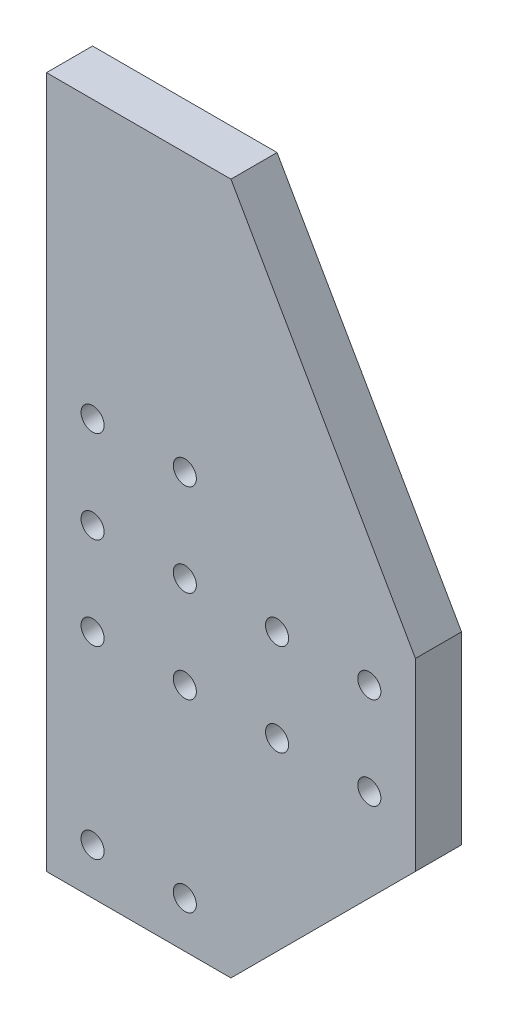
SolidWorks part; units mm, degrees
ref_plane "Front Plane" through (0, 0, 0) normal (0, 0, 1) x (1, 0, 0)
ref_plane "Top Plane" through (0, 0, 0) normal (0, 1, 0) x (1, 0, 0)
ref_plane "Right Plane" through (0, 0, 0) normal (1, 0, 0) x (0, 0, -1)
sketch "Sketch1" plane through (0, 0, 0) normal (0, 0, 1) x (1, 0, 0)
  line L0 (0, 0) -> (40, 0)
  line L1 (40, 0) -> (80, 40)
  line L2 (80, 40) -> (80, 80)
  line L3 (80, 80) -> (40, 150)
  line L4 (40, 150) -> (0, 150)
  line L5 (0, 150) -> (0, 0)
  dimension "D1" = 80
  dimension "D2" = 40
  dimension "D3" = 40
  dimension "D4" = 40
  dimension "D5" = 70
  dimension "D6" = 40
extrude "Boss-Extrude1" add sketch "Sketch1" along normal blind 10
sketch "Sketch2" plane through (0, 0, 10) normal (0, 0, 1) x (1, 0, 0)
  line L0 (0, 0) -> (40, 0) construction
  line L1 (80, 40) -> (80, 80) construction
  line L2 (0, 150) -> (0, 0) construction
  circle A0 centre (10, 10) radius 2.5
  circle A1 centre (30, 10) radius 2.5
  circle A2 centre (10, 50) radius 2.5
  circle A3 centre (70, 70) radius 2.5
  circle A4 centre (50, 70) radius 2.5
  circle A5 centre (50, 50) radius 2.5
  circle A6 centre (30, 50) radius 2.5
  circle A7 centre (70, 50) radius 2.5
  circle A8 centre (30, 90) radius 2.5
  circle A9 centre (10, 90) radius 2.5
  circle A10 centre (10, 70) radius 2.5
  circle A11 centre (30, 70) radius 2.5
  point P24 (0, 0)
  point P25 (0, 0)
  point P26 (0, 0)
  point P27 (0, 0)
  point P28 (0, 0)
  point P29 (0, 0)
  point P34 (0, 0)
  point P35 (0, 0)
  point P36 (0, 0)
  point P39 (0, 0)
  dimension "D1" = 10
  dimension "D10" = 5
  dimension "D2" = 40
  dimension "D3" = 20
  dimension "D4" = 10
  dimension "D5" = 20
  dimension "D6" = 20
  dimension "D7" = 20
  dimension "D8" = 50
  dimension "D9" = 20
  dimension "D11" = 10
extrude "Cut-Extrude1" cut sketch "Sketch2" against normal up to next
